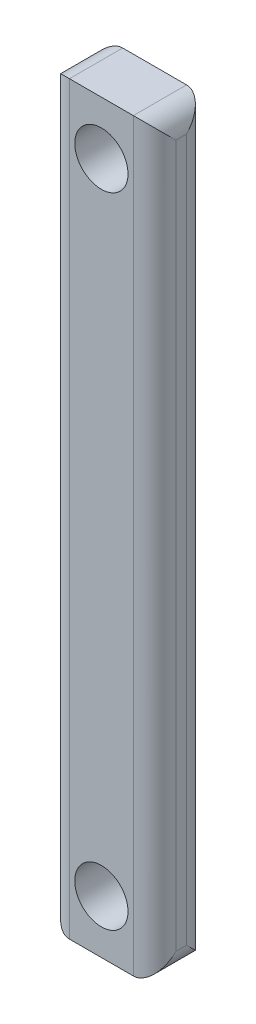
SolidWorks part; units mm, degrees
ref_plane "Front Plane" through (0, 0, 0) normal (0, 0, 1) x (1, 0, 0)
ref_plane "Top Plane" through (0, 0, 0) normal (0, 1, 0) x (1, 0, 0)
ref_plane "Right Plane" through (0, 0, 0) normal (1, 0, 0) x (0, 0, -1)
sketch "Sketch1" plane through (0, 0, 0) normal (0, 0, 1) x (1, 0, 0)
  line L1 (0, 0) -> (-50, 0)
  line L2 (0, 0) -> (0, 350)
  line L3 (0, 350) -> (-50, 350)
  line L4 (-50, 0) -> (-50, 350)
  circle A0 centre (-25, 25) radius 12.5
  circle A1 centre (-25, 325) radius 12.5
  dimension "D3" = 25
  dimension "D1" = 350
  dimension "D2" = 50
  dimension "D4" = 25
  dimension "D5" = 25
  dimension "D6" = 25
extrude "Boss-Extrude1" add sketch "Sketch1" along normal blind 25
fillet "Fillet1" radius 10 8 edges at (0, 175, 0) (-50, 175, 0) (-50, 175, 25) (0, 175, 25) (0, 0, 12.5) (-50, 0, 12.5) (0, 350, 12.5) (-50, 350, 12.5)
